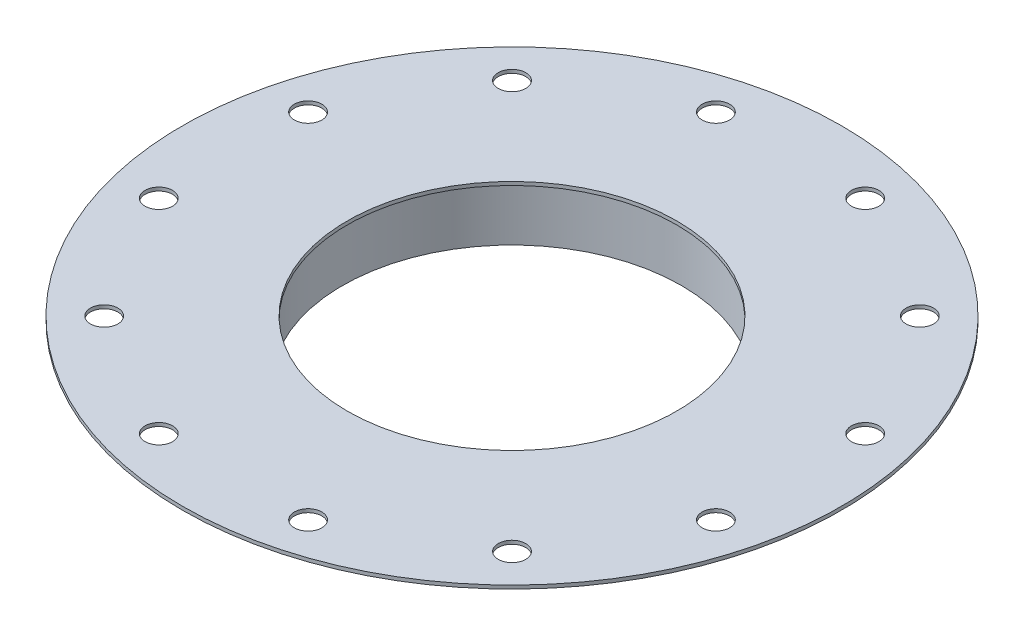
SolidWorks part; units mm, degrees
ref_plane "Front Plane" through (0, 0, 0) normal (0, 0, 1) x (1, 0, 0)
ref_plane "Top Plane" through (0, 0, 0) normal (0, 1, 0) x (1, 0, 0)
ref_plane "Right Plane" through (0, 0, 0) normal (1, 0, 0) x (0, 0, -1)
sketch "Sketch1" plane through (0, 0, 0) normal (0, 1, 0) x (1, 0, 0)
  line L0 (0, 300) -> (0, -300)
  line L1 (0, 600) -> (0, -600)
  arc A0 (0, 300) -> (0, -300) centre (0, 0) cw
  arc A1 (0, 450) -> (0, -450) centre (0, 0) cw
  arc A2 (0, 600) -> (0, -600) centre (0, 0) cw
  circle A3 centre (0, 0) radius 600
  circle A4 centre (0, 0) radius 450
  circle A5 centre (0, 0) radius 300
  point P8 (0, 0)
  dimension "D1" = 600
  dimension "D2" = 150
  dimension "D3" = 150
extrude "Boss-Extrude1" add sketch "Sketch1" along normal blind 6.35 contours A1 L1 A0 | A4 L1 A3 | A5 L1 A4
sketch "Sketch2" plane through (0, 6.35, 0) normal (0, 1, 0) x (1, 0, 0)
  line L0 (0, 0) -> (0, 600) construction
  line L1 (0, 0) -> (135.88, 507.1111) construction
  line L2 (0, 0) -> (135.88, 507.1111) construction
  line L3 (0, 0) -> (135.88, 507.1111) construction
  line L4 (0, 0) -> (371.2311, 371.2311) construction
  line L5 (0, 0) -> (-135.88, 507.1111) construction
  circle A0 centre (135.88, 507.1111) radius 25
  circle A1 centre (0, 0) radius 525 construction
  circle A2 centre (-135.88, 507.1111) radius 25
  circle A3 centre (371.2311, 371.2311) radius 25
  circle A4 centre (507.1111, 135.88) radius 25
  circle A5 centre (507.1111, -135.88) radius 25
  circle A6 centre (371.2311, -371.2311) radius 25
  circle A7 centre (135.88, -507.1111) radius 25
  circle A8 centre (0, 0) radius 600 construction
  circle A9 centre (-371.2311, 371.2311) radius 25
  circle A10 centre (-507.1111, 135.88) radius 25
  circle A11 centre (-507.1111, -135.88) radius 25
  circle A12 centre (-371.2311, -371.2311) radius 25
  circle A13 centre (-135.88, -507.1111) radius 25
  dimension "D1" = 50
  dimension "D2" = 75
  dimension "D3" = 15
  dimension "D5" = 30
  dimension "D7" = 30
  dimension "D4" = 6
  dimension "D6" = 7
extrude "Cut-Extrude1" cut sketch "Sketch2" against normal through all both and the other way through all
sketch "Sketch3" plane through (0, 0, 0) normal (0, -1, 0) x (1, 0, 0)
  circle A0 centre (0, 0) radius 315
  circle A1 centre (0, 0) radius 308.65
  dimension "D1" = 630
  dimension "D2" = 6.35
extrude "Boss-Extrude2" add sketch "Sketch3" along normal blind 100
equation "\"hatchHoleDiameter\"= 600mm"
equation "\"hullThickness\"= 150mm"
equation "\"gasketHullInterconnectWidth\"= 100mm"
equation "\"collarThickness\"= 15"
equation "\"hatchTunnelLength\"=200"
equation "\"oRingDiameter\"=2"
equation "\"boltPatternRadiusInterconnect\"=500"
equation "\"interconnectBoltDiameter\"=30"
equation "\"hatchShaftDiameter\"=20"
equation "\"hatchMinima\"=50"
equation "\"hullDiameter\"=2000"
equation "\"hatchMaxima\"=180"
equation "\"bushingFlatHatch\"=15"
equation "\"hingePivotDiameter\"=20"
equation "\"handleWidth\"=250"
equation "\"handleHeight\"=160"
equation "\"handleThickness\"=25"
equation "\"FrameLength\"= 4300"
equation "\"FrameMidLength\"= 3000"
equation "\"TubeOD\"= 100"
equation "\"FrameBackFlat\"= 800"
equation "\"TubeWall\"=15"
equation "\"TopMemberAngle\"=120"
equation "\"FrameHight\"= 2500"
equation "\"D1@Sketch1\"=\"hatchHoleDiameter\""
equation "\"D2@Sketch1\"=\"hullThickness\""
equation "\"D3@Sketch1\"=\"hullThickness\""
equation "\"D1@Sketch3\"=\"hatchHoleDiameter\"+ 2* \"collarThickness\""
